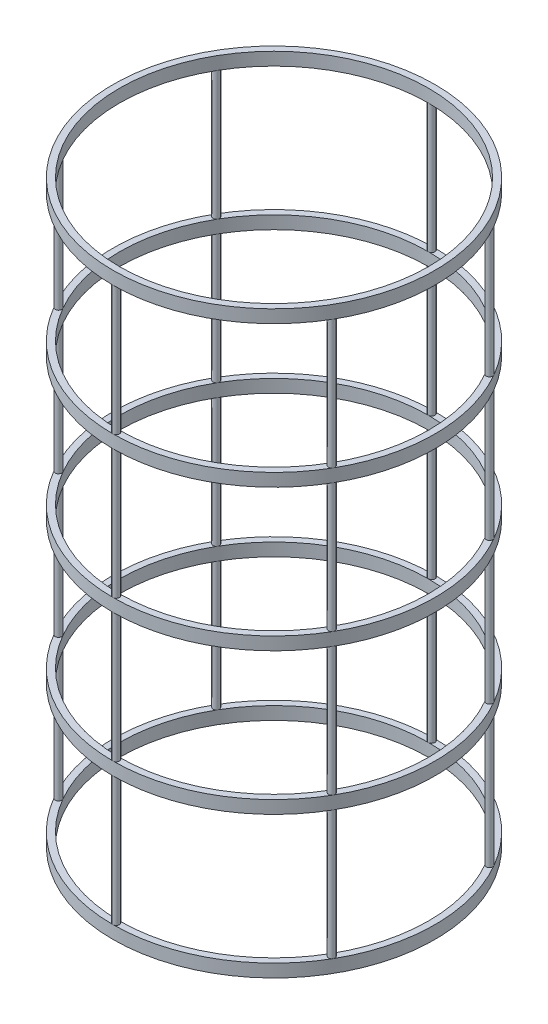
SolidWorks part; units mm, degrees
ref_plane "Front Plane" through (0, 0, 0) normal (0, 0, 1) x (1, 0, 0)
ref_plane "Top Plane" through (0, 0, 0) normal (0, 1, 0) x (1, 0, 0)
ref_plane "Right Plane" through (0, 0, 0) normal (1, 0, 0) x (0, 0, -1)
sketch "Sketch1" plane through (0, 0, 0) normal (0, 1, 0) x (1, 0, 0)
  circle A0 centre (0, 0) radius 125
  circle A1 centre (0, 0) radius 120
  dimension "D1" = 250
  dimension "D2" = 240
extrude "Boss-Extrude1" add sketch "Sketch1" along normal blind 10
sketch "Sketch2" plane through (0, 10, 0) normal (0, 1, 0) x (1, 0, 0)
  line L0 (0, 131.7359) -> (0, -136.902) construction
  line L1 (-168.2356, 0) -> (156.1065, 0) construction
  circle A0 centre (0, 122.5) radius 2.5
  circle A1 centre (0, 0) radius 125 construction
  circle A2 centre (0, 0) radius 120 construction
  circle A3 centre (106.0881, 61.25) radius 2.5
  circle A4 centre (106.0881, -61.25) radius 2.5
  circle A5 centre (0, -122.5) radius 2.5
  circle A6 centre (-106.0881, -61.25) radius 2.5
  circle A7 centre (-106.0881, 61.25) radius 2.5
  point P23 (0, 0)
  dimension "D1" = 6
extrude "Boss-Extrude2" add sketch "Sketch2" along normal blind 100
sketch "Sketch3" plane through (0, 110, 0) normal (0, 1, 0) x (1, 0, 0)
  circle A0 centre (0, 0) radius 120
  circle A1 centre (0, 0) radius 125
  dimension "D1" = 240
  dimension "D2" = 250
extrude "Boss-Extrude3" add sketch "Sketch3" along normal blind 10
sketch "Sketch4" plane through (0, 120, 0) normal (0, 1, 0) x (1, 0, 0)
  line L0 (0, 133.982) -> (0, -16.5091) construction
  circle A0 centre (0, 122.5) radius 2.5
  circle A1 centre (0, 0) radius 125 construction
  circle A2 centre (0, 0) radius 120 construction
  circle A3 centre (106.0881, 61.25) radius 2.5
  circle A4 centre (106.0881, -61.25) radius 2.5
  circle A5 centre (0, -122.5) radius 2.5
  circle A6 centre (-106.0881, -61.25) radius 2.5
  circle A7 centre (-106.0881, 61.25) radius 2.5
  point P21 (0, 0)
  dimension "D1" = 6
extrude "Boss-Extrude4" add sketch "Sketch4" along normal blind 100 contours A0 | A7 | A6 | A5 | A4 | A3
sketch "Sketch5" plane through (0, 220, 0) normal (0, 1, 0) x (1, 0, 0)
  circle A0 centre (0, 0) radius 120
  circle A1 centre (0, 0) radius 125
  dimension "D1" = 240
  dimension "D2" = 250
extrude "Boss-Extrude5" add sketch "Sketch5" along normal blind 10
sketch "Sketch6" plane through (0, 230, 0) normal (0, 1, 0) x (1, 0, 0)
  line L0 (0, 131.5113) -> (0, -10.8938) construction
  circle A0 centre (0, 122.5) radius 2.5
  circle A1 centre (0, 0) radius 125 construction
  circle A2 centre (0, 0) radius 120 construction
  circle A3 centre (106.0881, 61.25) radius 2.5
  circle A4 centre (106.0881, -61.25) radius 2.5
  circle A5 centre (0, -122.5) radius 2.5
  circle A6 centre (-106.0881, -61.25) radius 2.5
  circle A7 centre (-106.0881, 61.25) radius 2.5
  point P21 (0, 0)
  dimension "D1" = 6
extrude "Boss-Extrude6" add sketch "Sketch6" along normal blind 100
sketch "Sketch7" plane through (0, 330, 0) normal (0, 1, 0) x (1, 0, 0)
  circle A0 centre (0, 0) radius 120
  circle A1 centre (0, 0) radius 125
  dimension "D1" = 240
  dimension "D2" = 250
extrude "Boss-Extrude7" add sketch "Sketch7" along normal blind 10
sketch "Sketch8" plane through (0, 340, 0) normal (0, 1, 0) x (1, 0, 0)
  line L0 (0, 131.9605) -> (0, -27.9644) construction
  circle A0 centre (0, 122.5) radius 2.5
  circle A1 centre (0, 0) radius 125 construction
  circle A2 centre (0, 0) radius 120 construction
  circle A3 centre (106.0881, 61.25) radius 2.5
  circle A4 centre (106.0881, -61.25) radius 2.5
  circle A5 centre (0, -122.5) radius 2.5
  circle A6 centre (-106.0881, -61.25) radius 2.5
  circle A7 centre (-106.0881, 61.25) radius 2.5
  point P21 (0, 0)
  dimension "D1" = 6
extrude "Boss-Extrude8" add sketch "Sketch8" along normal blind 100
sketch "Sketch9" plane through (0, 440, 0) normal (0, 1, 0) x (1, 0, 0)
  circle A0 centre (0, 0) radius 120
  circle A1 centre (0, 0) radius 125
  dimension "D1" = 240
  dimension "D2" = 250
extrude "Boss-Extrude9" add sketch "Sketch9" along normal blind 10
